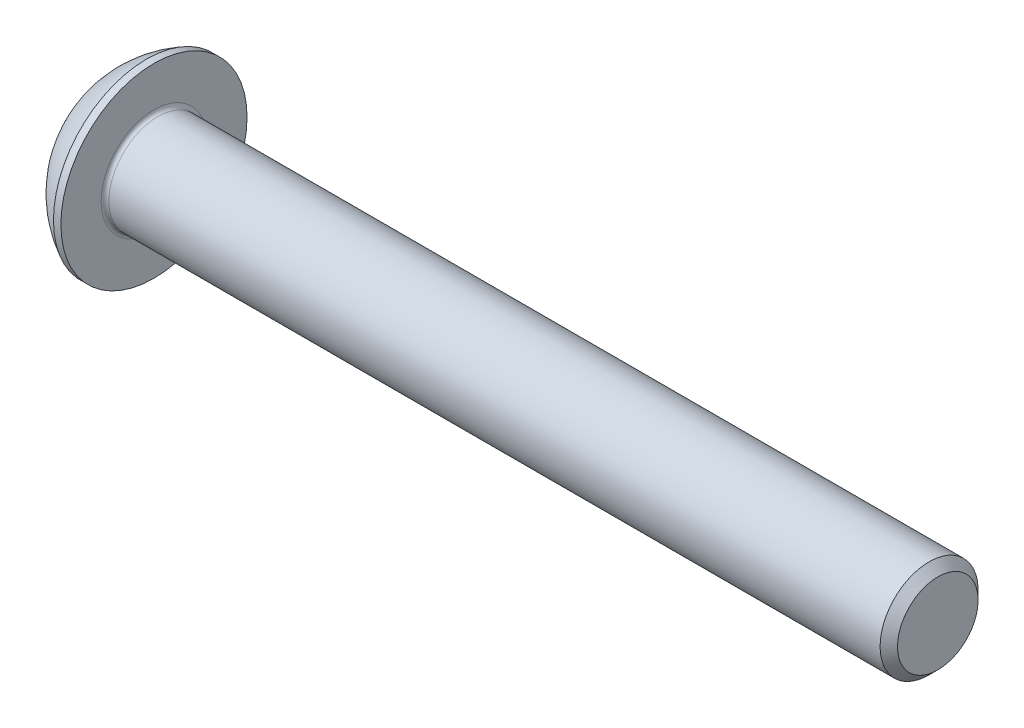
SolidWorks part; units mm, degrees
ref_plane "Plane1" through (0, 0, 0) normal (0, 0, 1) x (1, 0, 0)
ref_plane "Plane2" through (0, 0, 0) normal (0, 1, 0) x (1, 0, 0)
ref_plane "Plane3" through (0, 0, 0) normal (1, 0, 0) x (0, 0, -1)
sketch "BodySke" plane through (0, 0, 0) normal (0, 0, 1) x (1, 0, 0)
  line L0 (42.75, 0) -> (42.75, 2.055)
  line L1 (42.305, 2.5) -> (2.75, 2.5)
  line L2 (2.75, 2.5) -> (2.75, 4.75)
  line L3 (2.75, 4.75) -> (2.37, 4.75)
  line L4 (0, 0) -> (101.6, 0) construction
  line L5 (2.75, -4.75) -> (2.37, -4.75) construction
  line L6 (55.6768, -2.5) -> (2.75, -2.5) construction
  line L7 (42.75, 0) -> (0, 0)
  line L8 (0, 2.375) -> (0, -2.375) construction
  line L9 (0, 0) -> (0, 2.375)
  line L10 (42.75, 2.055) -> (42.305, 2.5)
  line L11 (42.75, -2.055) -> (42.305, -2.5) construction
  line L12 (3.55, 9.525) -> (3.55, -2.5) construction
  line L13 (-3357.25, 9.525) -> (-3357.25, -2.5) construction
  arc A1 (0, 2.375) -> (2.37, 4.75) centre (4.755, 0) cw
  dimension "D1" = 4.75
  dimension "Diameter" = 5
  dimension "Length" = 40
  dimension "Head_dia" = 9.5
  dimension "Head_ht" = 2.75
  dimension "Head_side_ht" = 0.38
  dimension "Minor_dia" = 4.11
  dimension "Body_ch_ang" = 45
  dimension "Advance" = 0.8
  dimension "Thread_nom" = 3400
revolve "BaseBody" add sketch "BodySke" angle 360 about L4
cosmetic thread "ThreadCosmetic" parameters "Thread_length"=38.4, "Thread_minor"=4.11
fillet "Fillet1" radius 0.2 1 edges at (2.75, 0, 2.5)
sketch "Sketch2" plane through (0, 0, 0) normal (0, 0, 1) x (1, 0, 0)
  line L0 (0, 1.5) -> (1.56, 1.5)
  line L1 (1.56, 1.5) -> (2.426, 0)
  line L3 (2.426, 0) -> (0, 0)
  line L4 (0, 0) -> (0, 1.5)
  line L5 (0, -1.5) -> (1.56, -1.5) construction
  line L6 (0, 0) -> (47.625, 0) construction
  dimension "D2" = 60
  dimension "PreBroach_depth" = 1.56
  dimension "PreBroach_dia" = 3
revolve "PreBroach" cut sketch "Sketch2" angle 360 about L6
sketch "Sketch3" plane through (0, 0, 0) normal (1, 0, 0) x (0, 0, -1)
  line L0 (-1.5, -0.866) -> (-1.5, 0.866)
  line L1 (-1.5, 0.866) -> (0, 1.7321)
  line L2 (0, 1.7321) -> (1.5, 0.866)
  line L3 (1.5, 0.866) -> (1.5, -0.866)
  line L4 (1.5, -0.866) -> (0, -1.7321)
  line L5 (0, -1.7321) -> (-1.5, -0.866)
  dimension "D1" = 1.5
  dimension "D2" = 1.5
  dimension "D3" = 3
  dimension "Hex_size" = 3
extrude "Hex" cut sketch "Sketch3" along normal blind 1.56
sketch "ThdSchSke" plane through (0, 0, 0) normal (0, 0, 1) x (1, 0, 0)
  line L0 (4.35, -2.055) -> (4.0384, -2.5)
  line L1 (4.35, -2.055) -> (4.6616, -2.5)
  line L2 (4.6616, -2.5) -> (4.6616, -3.125)
  line L3 (-3.175, 0) -> (5.1513, 0) construction
  line L5 (4.6616, -3.125) -> (4.0384, -3.125)
  line L6 (4.0384, -3.125) -> (4.0384, -2.5)
  dimension "Thread_minor" = 4.11
  dimension "Diameter" = 5
  dimension "Start" = 4.35
  dimension "SideAngle" = 55
  dimension "VeeAngle" = 70
  dimension "Overcut" = 6.25
revolve "ThreadSchematic" [suppressed] cut sketch "ThdSchSke" angle 360 about L3
pattern_linear "ThdSchPat" [suppressed]
equation "\"D1@BodySke\" = \"Head_dia@BodySke\" * .5"
equation "\"Thread_minor@ThreadCosmetic\" = \"Minor_dia@BodySke\""
equation "\"D1@Sketch3\" = \"Hex_size@Sketch3\" / 2"
equation "\"D2@Sketch3\" = \"D1@Sketch3\""
equation "\"D3@Sketch3\" = \"Hex_size@Sketch3\""
equation "\"Thread_length@ThreadCosmetic\" = ((sgn( (\"Length@BodySke\" - \"Advance@BodySke\" * 2.0) - \"Thread_nom@BodySke\" )-1)*( (\"Length@BodySke\" - \"Advance@BodySke\" * 2.0) - \"Thread_nom@BodySke\" ))/-2+ \"Thread_nom@BodySke\""
equation "\"Thread_minor@ThdSchSke\" = \"Minor_dia@BodySke\""
equation "\"Diameter@ThdSchSke\" = \"Diameter@BodySke\""
equation "\"Overcut@ThdSchSke\" = \"Diameter@BodySke\" * 1.25"
equation "\"Start@ThdSchSke\" = \"Head_ht@BodySke\" + \"Length@BodySke\" - \"Thread_length@ThreadCosmetic\"  '---Non-countersunk---"
equation "\"Num_threads@ThdSchPat\" = int( \"Thread_length@ThreadCosmetic\" / \"Advance@BodySke\" + 0.999 )  + 1"
equation "\"Advance@ThdSchPat\" = \"Thread_length@ThreadCosmetic\" /  (\"Num_threads@ThdSchPat\" - 1) 'relax it"
equation "\"Num_threads@ThdSchPat\" = \"Num_threads@ThdSchPat\" - sgn( \"Num_threads@ThdSchPat\" - 1) '---chamfered tips only---"
